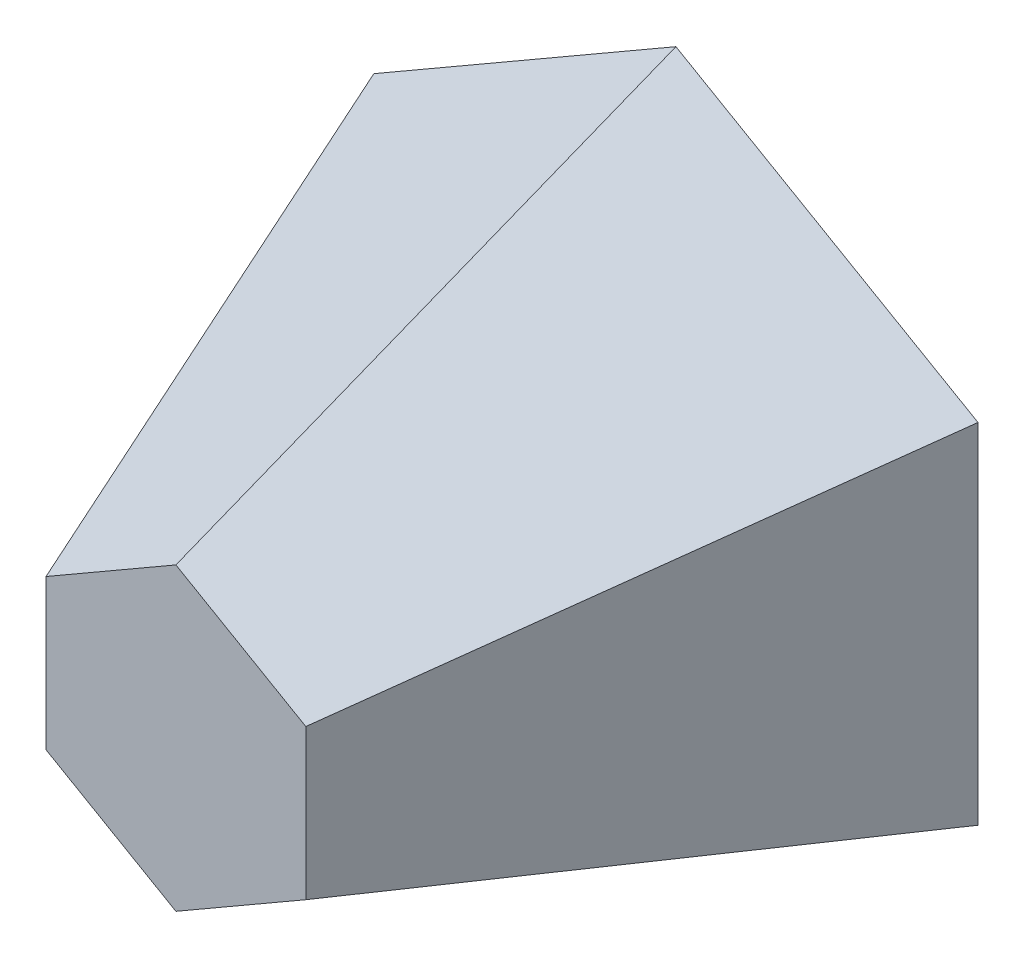
SolidWorks part; units mm, degrees
ref_plane "Alzado" through (0, 0, 0) normal (0, 0, 1) x (1, 0, 0)
ref_plane "Planta" through (0, 0, 0) normal (0, 1, 0) x (1, 0, 0)
ref_plane "Vista lateral" through (0, 0, 0) normal (1, 0, 0) x (0, 0, -1)
sketch "Croquis1" plane through (0, 0, 0) normal (0, 0, 1) x (1, 0, 0)
  line L1 (0, 75) -> (-64.9519, 37.5)
  line L2 (-64.9519, 37.5) -> (-64.9519, -37.5)
  line L3 (-64.9519, -37.5) -> (0, -75)
  line L4 (0, -75) -> (64.9519, -37.5)
  line L5 (64.9519, -37.5) -> (64.9519, 37.5)
  line L6 (64.9519, 37.5) -> (0, 75)
  circle A0 centre (0, 0) radius 75 construction
  dimension "D1" = 150
extrude "Saliente-Extruir1" add sketch "Croquis1" along normal mid plane 250
draft "Ángulo de salida1" type of draft neutral plane draft angle 19 faces to draft 6 face at (-32.476, 56.25, 0) face at (-64.9519, 0, 0) face at (-32.476, -56.25, 0) face at (32.476, 56.25, 0) face at (64.9519, 0, 0) face at (32.476, -56.25, 0) neutral plane through (0, 0, 125) neutral plane normal (0, 0, 1) parameters "D1"=19
shell "Vaciado1" thickness 1.4
